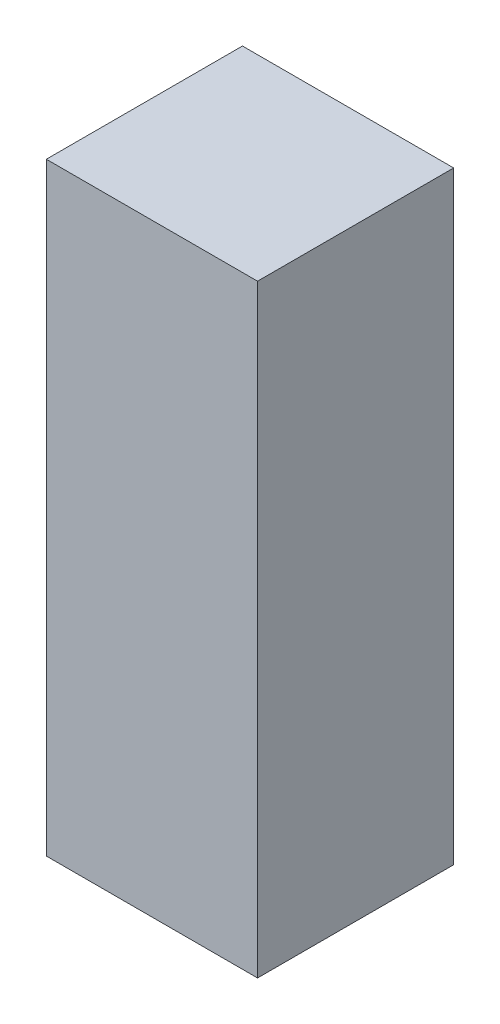
SolidWorks part; units mm, degrees
ref_plane "Front Plane" through (0, 0, 0) normal (0, 0, 1) x (1, 0, 0)
ref_plane "Top Plane" through (0, 0, 0) normal (0, 1, 0) x (1, 0, 0)
ref_plane "Right Plane" through (0, 0, 0) normal (1, 0, 0) x (0, 0, -1)
other "Configuration Table"
sketch "Sketch1" plane through (0, 0, 0) normal (0, 0, 1) x (1, 0, 0)
  line L1 (24, 1380) -> (38, 1380)
  line L2 (24, 1380) -> (24, 1420)
  line L3 (24, 1420) -> (38, 1420)
  line L4 (38, 1380) -> (38, 1420)
extrude "PRESS_kova_kapagi_mentese_1_1" add sketch "Sketch1" along normal blind 13 from offset 20 separate body
